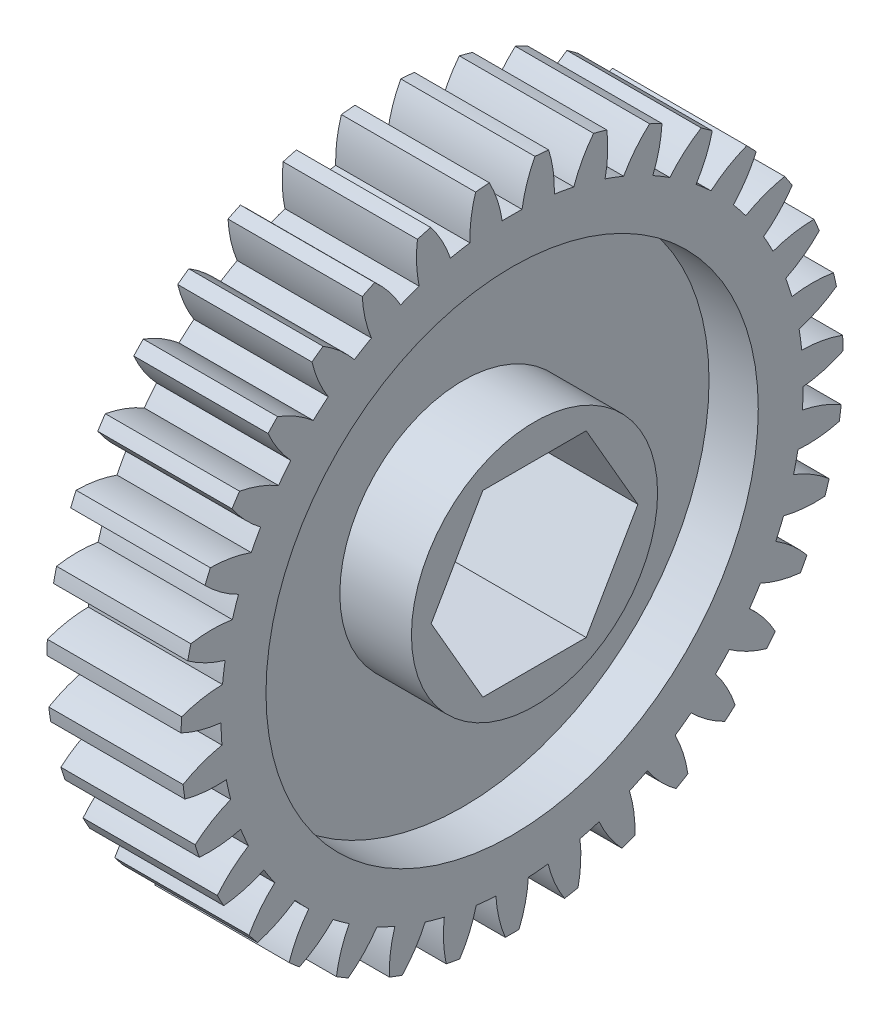
SolidWorks part; units mm, degrees
ref_plane "Front Plane" through (0, 0, 0) normal (0, 0, 1) x (1, 0, 0)
ref_plane "Top Plane" through (0, 0, 0) normal (0, 1, 0) x (1, 0, 0)
ref_plane "Right Plane" through (0, 0, 0) normal (1, 0, 0) x (0, 0, -1)
ref_plane "Plane1" through (0, 0, 0) normal (0, 0, -1) x (-1, 0, 0)
sketch "Sketch1" plane through (0, 0, 0) normal (0, 0, -1) x (-1, 0, 0)
  line L0 (-9.525, 23.495) -> (-9.525, 0)
  line L1 (-9.525, 0) -> (0, 0)
  line L2 (0, 0) -> (0, 23.495)
  line L3 (0, 23.495) -> (-9.525, 23.495)
  line L4 (-9.525, 0) -> (0, 0) construction
revolve "Revolve1" add sketch "Sketch1" angle 360 about L4
sketch "Sketch2" plane through (0, 0, 0) normal (-1, 0, 0) x (0, 0, 1)
  arc A0 (-2.5904, 23.3518) -> (-5.78, 22.7729) centre (0, 0) ccw
  arc A1 (-5.78, 22.7729) -> (-4.3772, 20.181) centre (-12.7888, 17.3041) cw
  arc A2 (-4.3772, 20.181) -> (-2.993, 20.4321) centre (0, 0) cw
  arc A3 (-2.993, 20.4321) -> (-2.5904, 23.3518) centre (5.8931, 20.6944) cw
extrude "Cut-Extrude1" cut sketch "Sketch2" against normal through all
sketch "Sketch3" plane through (0, 0, 0) normal (-1, 0, 0) x (0, 0, 1)
  arc A0 (1.6208, 23.439) -> (-1.6208, 23.439) centre (0, 0) ccw
  arc A1 (-1.6208, 23.439) -> (-0.7034, 20.6382) centre (-9.4935, 19.3095) cw
  arc A2 (-0.7034, 20.6382) -> (0.7034, 20.6382) centre (0, 0) cw
  arc A3 (0.7034, 20.6382) -> (1.6208, 23.439) centre (9.4935, 19.3095) cw
extrude "Cut-Extrude2" cut sketch "Sketch3" against normal through all
sketch "Sketch4" plane through (0, 0, 0) normal (-1, 0, 0) x (0, 0, 1)
  arc A0 (5.78, 22.7729) -> (2.5904, 23.3518) centre (0, 0) ccw
  arc A1 (2.5904, 23.3518) -> (2.993, 20.4321) centre (-5.8931, 20.6944) cw
  arc A2 (2.993, 20.4321) -> (4.3772, 20.181) centre (0, 0) cw
  arc A3 (4.3772, 20.181) -> (5.78, 22.7729) centre (12.7888, 17.3041) cw
extrude "Cut-Extrude3" cut sketch "Sketch4" against normal through all
sketch "Sketch5" plane through (0, 0, 0) normal (-1, 0, 0) x (0, 0, 1)
  arc A0 (9.7534, 21.3749) -> (6.7184, 22.5139) centre (0, 0) ccw
  arc A1 (6.7184, 22.5139) -> (6.5932, 19.5694) centre (-2.1033, 21.414) cw
  arc A2 (6.5932, 19.5694) -> (7.9103, 19.0751) centre (0, 0) cw
  arc A3 (7.9103, 19.0751) -> (9.7534, 21.3749) centre (15.673, 14.7425) cw
extrude "Cut-Extrude4" cut sketch "Sketch5" against normal through all
sketch "Sketch6" plane through (0, 0, 0) normal (-1, 0, 0) x (0, 0, 1)
  arc A0 (13.4132, 19.2899) -> (10.6305, 20.9525) centre (0, 0) ccw
  arc A1 (10.6305, 20.9525) -> (9.9815, 18.0776) centre (1.7541, 21.4455) cw
  arc A2 (9.9815, 18.0776) -> (11.1891, 17.3561) centre (0, 0) cw
  arc A3 (11.1891, 17.3561) -> (13.4132, 19.2899) centre (18.0535, 11.707) cw
extrude "Cut-Extrude5" cut sketch "Sketch6" against normal through all
sketch "Sketch7" plane through (0, 0, 0) normal (-1, 0, 0) x (0, 0, 1)
  arc A0 (16.642, 16.5849) -> (14.2009, 18.7177) centre (0, 0) ccw
  arc A1 (14.2009, 18.7177) -> (13.049, 16.0048) centre (5.5552, 20.7876) cw
  arc A2 (13.049, 16.0048) -> (14.1084, 15.0793) centre (0, 0) cw
  arc A3 (14.1084, 15.0793) -> (16.642, 16.5849) centre (19.8538, 8.2953) cw
extrude "Cut-Extrude6" cut sketch "Sketch7" against normal through all
sketch "Sketch8" plane through (0, 0, 0) normal (-1, 0, 0) x (0, 0, 1)
  arc A0 (19.3359, 13.3468) -> (17.3148, 15.8812) centre (0, 0) ccw
  arc A1 (17.3148, 15.8812) -> (15.6971, 13.4176) centre (9.1777, 19.4616) cw
  arc A2 (15.6971, 13.4176) -> (16.5742, 12.3178) centre (0, 0) cw
  arc A3 (16.5742, 12.3178) -> (19.3359, 13.3468) centre (21.0159, 4.617) cw
extrude "Cut-Extrude7" cut sketch "Sketch8" against normal through all
sketch "Sketch9" plane through (0, 0, 0) normal (-1, 0, 0) x (0, 0, 1)
  arc A0 (21.4084, 9.6797) -> (19.8722, 12.5343) centre (0, 0) ccw
  arc A1 (19.8722, 12.5343) -> (17.8406, 10.3992) centre (12.5052, 17.5101) cw
  arc A2 (17.8406, 10.3992) -> (18.5072, 9.1604) centre (0, 0) cw
  arc A3 (18.5072, 9.1604) -> (21.4084, 9.6797) centre (21.5026, 0.7902) cw
extrude "Cut-Extrude8" cut sketch "Sketch9" against normal through all
sketch "Sketch10" plane through (0, 0, 0) normal (-1, 0, 0) x (0, 0, 1)
  arc A0 (22.7927, 5.7016) -> (21.791, 8.7845) centre (0, 0) ccw
  arc A1 (21.791, 8.7845) -> (19.4108, 7.0465) centre (15.4308, 14.9958) cw
  arc A2 (19.4108, 7.0465) -> (19.8455, 5.7086) centre (0, 0) cw
  arc A3 (19.8455, 5.7086) -> (22.7927, 5.7016) centre (21.2981, -3.0619) cw
extrude "Cut-Extrude9" cut sketch "Sketch10" against normal through all
sketch "Sketch11" plane through (0, 0, 0) normal (-1, 0, 0) x (0, 0, 1)
  arc A0 (23.4445, 1.5401) -> (23.0093, 4.7524) centre (0, 0) ccw
  arc A1 (23.0093, 4.7524) -> (20.357, 3.4673) centre (17.8604, 11.9996) cw
  arc A2 (20.357, 3.4673) -> (20.5459, 2.0733) centre (0, 0) cw
  arc A3 (20.5459, 2.0733) -> (23.4445, 1.5401) centre (20.4091, -6.8156) cw
extrude "Cut-Extrude10" cut sketch "Sketch11" against normal through all
sketch "Sketch12" plane through (0, 0, 0) normal (-1, 0, 0) x (0, 0, 1)
  arc A0 (23.3427, -2.6708) -> (23.4881, 0.5676) centre (0, 0) ccw
  arc A1 (23.4881, 0.5676) -> (20.649, -0.2233) centre (19.716, 8.6176) cw
  arc A2 (20.649, -0.2233) -> (20.5859, -1.6286) centre (0, 0) cw
  arc A3 (20.5859, -1.6286) -> (23.3427, -2.6708) centre (18.8642, -10.3503) cw
extrude "Cut-Extrude11" cut sketch "Sketch12" against normal through all
sketch "Sketch13" plane through (0, 0, 0) normal (-1, 0, 0) x (0, 0, 1)
  arc A0 (22.4907, -6.7959) -> (23.212, -3.6355) centre (0, 0) ccw
  arc A1 (23.212, -3.6355) -> (20.2773, -3.9067) centre (20.9379, 4.9587) cw
  arc A2 (20.2773, -3.9067) -> (19.9643, -5.2782) centre (0, 0) cw
  arc A3 (19.9643, -5.2782) -> (22.4907, -6.7959) centre (16.7129, -13.5523) cw
extrude "Cut-Extrude12" cut sketch "Sketch13" against normal through all
sketch "Sketch14" plane through (0, 0, 0) normal (-1, 0, 0) x (0, 0, 1)
  arc A0 (20.9158, -10.7025) -> (22.1899, -7.7217) centre (0, 0) ccw
  arc A1 (22.1899, -7.7217) -> (19.2539, -7.4646) centre (21.4868, 1.1404) cw
  arc A2 (19.2539, -7.4646) -> (18.701, -8.7581) centre (0, 0) cw
  arc A3 (18.701, -8.7581) -> (20.9158, -10.7025) centre (14.0245, -16.3187) cw
extrude "Cut-Extrude13" cut sketch "Sketch14" against normal through all
sketch "Sketch15" plane through (0, 0, 0) normal (-1, 0, 0) x (0, 0, 1)
  arc A0 (18.6687, -14.2652) -> (20.4545, -11.5598) centre (0, 0) ccw
  arc A1 (20.4545, -11.5598) -> (17.6116, -10.7825) centre (21.3452, -2.7145) cw
  arc A2 (17.6116, -10.7825) -> (16.8366, -11.9565) centre (0, 0) cw
  arc A3 (16.8366, -11.9565) -> (18.6687, -14.2652) centre (10.8853, -18.5606) cw
extrude "Cut-Extrude14" cut sketch "Sketch15" against normal through all
sketch "Sketch16" plane through (0, 0, 0) normal (-1, 0, 0) x (0, 0, 1)
  arc A0 (15.8215, -17.3694) -> (18.0617, -15.0263) centre (0, 0) ccw
  arc A1 (18.0617, -15.0263) -> (15.4033, -13.7539) centre (20.5174, -6.4822) cw
  arc A2 (15.4033, -13.7539) -> (14.4311, -14.7707) centre (0, 0) cw
  arc A3 (14.4311, -14.7707) -> (15.8215, -17.3694) centre (7.3962, -20.206) cw
extrude "Cut-Extrude15" cut sketch "Sketch16" against normal through all
sketch "Sketch17" plane through (0, 0, 0) normal (-1, 0, 0) x (0, 0, 1)
  arc A0 (12.4658, -19.9153) -> (15.0884, -18.0099) centre (0, 0) ccw
  arc A1 (15.0884, -18.0099) -> (12.6999, -16.2832) centre (19.0303, -10.0416) cw
  arc A2 (12.6999, -16.2832) -> (11.5618, -17.1101) centre (0, 0) cw
  arc A3 (11.5618, -17.1101) -> (12.4658, -19.9153) centre (3.6694, -21.2019) cw
extrude "Cut-Extrude16" cut sketch "Sketch17" against normal through all
sketch "Sketch18" plane through (0, 0, 0) normal (-1, 0, 0) x (0, 0, 1)
  arc A0 (8.7095, -21.8211) -> (11.6301, -20.4146) centre (0, 0) ccw
  arc A1 (11.6301, -20.4146) -> (9.5883, -18.2892) centre (16.9315, -13.2782) cw
  arc A2 (9.5883, -18.2892) -> (8.3209, -18.8996) centre (0, 0) cw
  arc A3 (8.3209, -18.8996) -> (8.7095, -21.8211) centre (-0.1753, -21.5164) cw
extrude "Cut-Extrude17" cut sketch "Sketch18" against normal through all
sketch "Sketch19" plane through (0, 0, 0) normal (-1, 0, 0) x (0, 0, 1)
  arc A0 (4.6732, -23.0255) -> (7.7981, -22.1632) centre (0, 0) ccw
  arc A1 (7.7981, -22.1632) -> (6.1685, -19.7074) centre (14.2884, -16.088) cw
  arc A2 (6.1685, -19.7074) -> (4.8125, -20.0816) centre (0, 0) cw
  arc A3 (4.8125, -20.0816) -> (4.6732, -23.0255) centre (-4.0144, -21.1393) cw
extrude "Cut-Extrude18" cut sketch "Sketch19" against normal through all
sketch "Sketch20" plane through (0, 0, 0) normal (-1, 0, 0) x (0, 0, 1)
  arc A0 (0.4868, -23.49) -> (3.7154, -23.1994) centre (0, 0) ccw
  arc A1 (3.7154, -23.1994) -> (2.5505, -20.4921) centre (11.1862, -18.3808) cw
  arc A2 (2.5505, -20.4921) -> (1.1495, -20.6182) centre (0, 0) cw
  arc A3 (1.1495, -20.6182) -> (0.4868, -23.49) centre (-7.7244, -20.0828) cw
extrude "Cut-Extrude19" cut sketch "Sketch20" against normal through all
sketch "Sketch21" plane through (0, 0, 0) normal (-1, 0, 0) x (0, 0, 1)
  arc A0 (-3.7154, -23.1994) -> (-0.4868, -23.49) centre (0, 0) ccw
  arc A1 (-0.4868, -23.49) -> (-1.1495, -20.6182) centre (7.7244, -20.0828) cw
  arc A2 (-1.1495, -20.6182) -> (-2.5505, -20.4921) centre (0, 0) cw
  arc A3 (-2.5505, -20.4921) -> (-3.7154, -23.1994) centre (-11.1862, -18.3808) cw
extrude "Cut-Extrude20" cut sketch "Sketch21" against normal through all
sketch "Sketch22" plane through (0, 0, 0) normal (-1, 0, 0) x (0, 0, 1)
  arc A0 (-7.7981, -22.1632) -> (-4.6732, -23.0255) centre (0, 0) ccw
  arc A1 (-4.6732, -23.0255) -> (-4.8125, -20.0816) centre (4.0144, -21.1393) cw
  arc A2 (-4.8125, -20.0816) -> (-6.1685, -19.7074) centre (0, 0) cw
  arc A3 (-6.1685, -19.7074) -> (-7.7981, -22.1632) centre (-14.2884, -16.088) cw
extrude "Cut-Extrude21" cut sketch "Sketch22" against normal through all
sketch "Sketch23" plane through (0, 0, 0) normal (-1, 0, 0) x (0, 0, 1)
  arc A0 (-11.6301, -20.4146) -> (-8.7095, -21.8211) centre (0, 0) ccw
  arc A1 (-8.7095, -21.8211) -> (-8.3209, -18.8996) centre (0.1753, -21.5164) cw
  arc A2 (-8.3209, -18.8996) -> (-9.5883, -18.2892) centre (0, 0) cw
  arc A3 (-9.5883, -18.2892) -> (-11.6301, -20.4146) centre (-16.9315, -13.2782) cw
extrude "Cut-Extrude22" cut sketch "Sketch23" against normal through all
sketch "Sketch24" plane through (0, 0, 0) normal (-1, 0, 0) x (0, 0, 1)
  arc A0 (-15.0884, -18.0099) -> (-12.4658, -19.9153) centre (0, 0) ccw
  arc A1 (-12.4658, -19.9153) -> (-11.5618, -17.1101) centre (-3.6694, -21.2019) cw
  arc A2 (-11.5618, -17.1101) -> (-12.6999, -16.2832) centre (0, 0) cw
  arc A3 (-12.6999, -16.2832) -> (-15.0884, -18.0099) centre (-19.0303, -10.0416) cw
extrude "Cut-Extrude23" cut sketch "Sketch24" against normal through all
sketch "Sketch25" plane through (0, 0, 0) normal (-1, 0, 0) x (0, 0, 1)
  arc A0 (-18.0617, -15.0263) -> (-15.8215, -17.3694) centre (0, 0) ccw
  arc A1 (-15.8215, -17.3694) -> (-14.4311, -14.7707) centre (-7.3962, -20.206) cw
  arc A2 (-14.4311, -14.7707) -> (-15.4033, -13.7539) centre (0, 0) cw
  arc A3 (-15.4033, -13.7539) -> (-18.0617, -15.0263) centre (-20.5174, -6.4822) cw
extrude "Cut-Extrude24" cut sketch "Sketch25" against normal through all
sketch "Sketch26" plane through (0, 0, 0) normal (-1, 0, 0) x (0, 0, 1)
  arc A0 (-20.4545, -11.5598) -> (-18.6687, -14.2652) centre (0, 0) ccw
  arc A1 (-18.6687, -14.2652) -> (-16.8366, -11.9565) centre (-10.8853, -18.5606) cw
  arc A2 (-16.8366, -11.9565) -> (-17.6116, -10.7825) centre (0, 0) cw
  arc A3 (-17.6116, -10.7825) -> (-20.4545, -11.5598) centre (-21.3452, -2.7145) cw
extrude "Cut-Extrude25" cut sketch "Sketch26" against normal through all
sketch "Sketch27" plane through (0, 0, 0) normal (-1, 0, 0) x (0, 0, 1)
  arc A0 (-22.1899, -7.7217) -> (-20.9158, -10.7025) centre (0, 0) ccw
  arc A1 (-20.9158, -10.7025) -> (-18.701, -8.7581) centre (-14.0245, -16.3187) cw
  arc A2 (-18.701, -8.7581) -> (-19.2539, -7.4646) centre (0, 0) cw
  arc A3 (-19.2539, -7.4646) -> (-22.1899, -7.7217) centre (-21.4868, 1.1404) cw
extrude "Cut-Extrude26" cut sketch "Sketch27" against normal through all
sketch "Sketch28" plane through (0, 0, 0) normal (-1, 0, 0) x (0, 0, 1)
  arc A0 (-23.212, -3.6355) -> (-22.4907, -6.7959) centre (0, 0) ccw
  arc A1 (-22.4907, -6.7959) -> (-19.9643, -5.2782) centre (-16.7129, -13.5523) cw
  arc A2 (-19.9643, -5.2782) -> (-20.2773, -3.9067) centre (0, 0) cw
  arc A3 (-20.2773, -3.9067) -> (-23.212, -3.6355) centre (-20.9379, 4.9587) cw
extrude "Cut-Extrude27" cut sketch "Sketch28" against normal through all
sketch "Sketch29" plane through (0, 0, 0) normal (-1, 0, 0) x (0, 0, 1)
  arc A0 (-23.4881, 0.5676) -> (-23.3427, -2.6708) centre (0, 0) ccw
  arc A1 (-23.3427, -2.6708) -> (-20.5859, -1.6286) centre (-18.8642, -10.3503) cw
  arc A2 (-20.5859, -1.6286) -> (-20.649, -0.2233) centre (0, 0) cw
  arc A3 (-20.649, -0.2233) -> (-23.4881, 0.5676) centre (-19.716, 8.6176) cw
extrude "Cut-Extrude28" cut sketch "Sketch29" against normal through all
sketch "Sketch30" plane through (0, 0, 0) normal (-1, 0, 0) x (0, 0, 1)
  arc A0 (-23.0093, 4.7524) -> (-23.4445, 1.5401) centre (0, 0) ccw
  arc A1 (-23.4445, 1.5401) -> (-20.5459, 2.0733) centre (-20.4091, -6.8156) cw
  arc A2 (-20.5459, 2.0733) -> (-20.357, 3.4673) centre (0, 0) cw
  arc A3 (-20.357, 3.4673) -> (-23.0093, 4.7524) centre (-17.8604, 11.9996) cw
extrude "Cut-Extrude29" cut sketch "Sketch30" against normal through all
sketch "Sketch31" plane through (0, 0, 0) normal (-1, 0, 0) x (0, 0, 1)
  arc A0 (-21.791, 8.7845) -> (-22.7927, 5.7016) centre (0, 0) ccw
  arc A1 (-22.7927, 5.7016) -> (-19.8455, 5.7086) centre (-21.2981, -3.0619) cw
  arc A2 (-19.8455, 5.7086) -> (-19.4108, 7.0465) centre (0, 0) cw
  arc A3 (-19.4108, 7.0465) -> (-21.791, 8.7845) centre (-15.4308, 14.9958) cw
extrude "Cut-Extrude30" cut sketch "Sketch31" against normal through all
sketch "Sketch32" plane through (0, 0, 0) normal (-1, 0, 0) x (0, 0, 1)
  arc A0 (-19.8722, 12.5343) -> (-21.4084, 9.6797) centre (0, 0) ccw
  arc A1 (-21.4084, 9.6797) -> (-18.5072, 9.1604) centre (-21.5026, 0.7902) cw
  arc A2 (-18.5072, 9.1604) -> (-17.8406, 10.3992) centre (0, 0) cw
  arc A3 (-17.8406, 10.3992) -> (-19.8722, 12.5343) centre (-12.5052, 17.5101) cw
extrude "Cut-Extrude31" cut sketch "Sketch32" against normal through all
sketch "Sketch33" plane through (0, 0, 0) normal (-1, 0, 0) x (0, 0, 1)
  arc A0 (-17.3148, 15.8812) -> (-19.3359, 13.3468) centre (0, 0) ccw
  arc A1 (-19.3359, 13.3468) -> (-16.5742, 12.3178) centre (-21.0159, 4.617) cw
  arc A2 (-16.5742, 12.3178) -> (-15.6971, 13.4176) centre (0, 0) cw
  arc A3 (-15.6971, 13.4176) -> (-17.3148, 15.8812) centre (-9.1777, 19.4616) cw
extrude "Cut-Extrude32" cut sketch "Sketch33" against normal through all
sketch "Sketch34" plane through (0, 0, 0) normal (-1, 0, 0) x (0, 0, 1)
  arc A0 (-14.2009, 18.7177) -> (-16.642, 16.5849) centre (0, 0) ccw
  arc A1 (-16.642, 16.5849) -> (-14.1084, 15.0793) centre (-19.8538, 8.2953) cw
  arc A2 (-14.1084, 15.0793) -> (-13.049, 16.0048) centre (0, 0) cw
  arc A3 (-13.049, 16.0048) -> (-14.2009, 18.7177) centre (-5.5552, 20.7876) cw
extrude "Cut-Extrude33" cut sketch "Sketch34" against normal through all
sketch "Sketch35" plane through (0, 0, 0) normal (-1, 0, 0) x (0, 0, 1)
  arc A0 (-10.6305, 20.9525) -> (-13.4132, 19.2899) centre (0, 0) ccw
  arc A1 (-13.4132, 19.2899) -> (-11.1891, 17.3561) centre (-18.0535, 11.707) cw
  arc A2 (-11.1891, 17.3561) -> (-9.9815, 18.0776) centre (0, 0) cw
  arc A3 (-9.9815, 18.0776) -> (-10.6305, 20.9525) centre (-1.7541, 21.4455) cw
extrude "Cut-Extrude34" cut sketch "Sketch35" against normal through all
sketch "Sketch36" plane through (0, 0, 0) normal (-1, 0, 0) x (0, 0, 1)
  arc A0 (-6.7184, 22.5139) -> (-9.7534, 21.3749) centre (0, 0) ccw
  arc A1 (-9.7534, 21.3749) -> (-7.9103, 19.0751) centre (-15.673, 14.7425) cw
  arc A2 (-7.9103, 19.0751) -> (-6.5932, 19.5694) centre (0, 0) cw
  arc A3 (-6.5932, 19.5694) -> (-6.7184, 22.5139) centre (2.1033, 21.414) cw
extrude "Cut-Extrude35" cut sketch "Sketch36" against normal through all
hole_wizard "M30 Clearance Hole1" positions "Sketch38" profile "Sketch37" hole size "M30" standard "ANSI Metric"
sketch "Sketch38" plane through (9.525, 0, 0) normal (1, 0, 0) x (0, 0, -1)
  point P0 (0, 0)
sketch "Sketch37" plane through (9.525, 0, 0) normal (0, 1, 0) x (0, 0, -1)
  line L0 (0, 0) -> (0, 3.4925)
  line L1 (0, 3.4925) -> (17.4625, 3.4925)
  line L2 (17.4625, 3.4925) -> (17.4625, 0)
  line L5 (17.4625, 0) -> (0, 0)
  line L10 (0, 3.4925) -> (-17.4625, 3.4925) construction
  line L11 (0, -6.35) -> (0, 107.95) construction
  dimension "Hole Dia." = 34.925
  dimension "Hole Depth" = 3.4925
  dimension "Drill Angle" = 180
sketch "Sketch39" plane through (6.0325, 0, 0) normal (1, 0, 0) x (0, 0, -1)
  circle A0 centre (0, 0) radius 8.7312
extrude "Boss-Extrude1" add sketch "Sketch39" along normal blind 5.08
hole_wizard "M30 Clearance Hole2" positions "Sketch41" profile "Sketch40" hole size "M30" standard "ANSI Metric"
sketch "Sketch41" plane through (0, 0, 0) normal (-1, 0, 0) x (0, 0, 1)
  point P0 (0, 0)
sketch "Sketch40" plane through (0, 0, 0) normal (0, 1, 0) x (0, 0, 1)
  line L0 (0, 0) -> (0, 3.4925)
  line L1 (0, 3.4925) -> (17.4625, 3.4925)
  line L2 (17.4625, 3.4925) -> (17.4625, 0)
  line L5 (17.4625, 0) -> (0, 0)
  line L10 (0, 3.4925) -> (-17.4625, 3.4925) construction
  line L11 (0, -6.35) -> (0, 107.95) construction
  dimension "Hole Dia." = 34.925
  dimension "Hole Depth" = 3.4925
  dimension "Drill Angle" = 180
sketch "Sketch42" plane through (3.4925, 0, 0) normal (-1, 0, 0) x (0, 0, 1)
  circle A0 centre (0, 0) radius 8.7312
extrude "Boss-Extrude2" add sketch "Sketch42" along normal blind 5.08
sketch "Sketch43" plane through (-1.5875, 0, 0) normal (-1, 0, 0) x (0, 0, 1)
  line L0 (-3.6662, -6.35) -> (3.6662, -6.35)
  line L1 (3.6662, -6.35) -> (7.3323, 0)
  line L2 (7.3323, 0) -> (3.6662, 6.35)
  line L3 (3.6662, 6.35) -> (-3.6662, 6.35)
  line L4 (-3.6662, 6.35) -> (-7.3323, 0)
  line L5 (-7.3323, 0) -> (-3.6662, -6.35)
extrude "Cut-Extrude36" cut sketch "Sketch43" against normal through all
